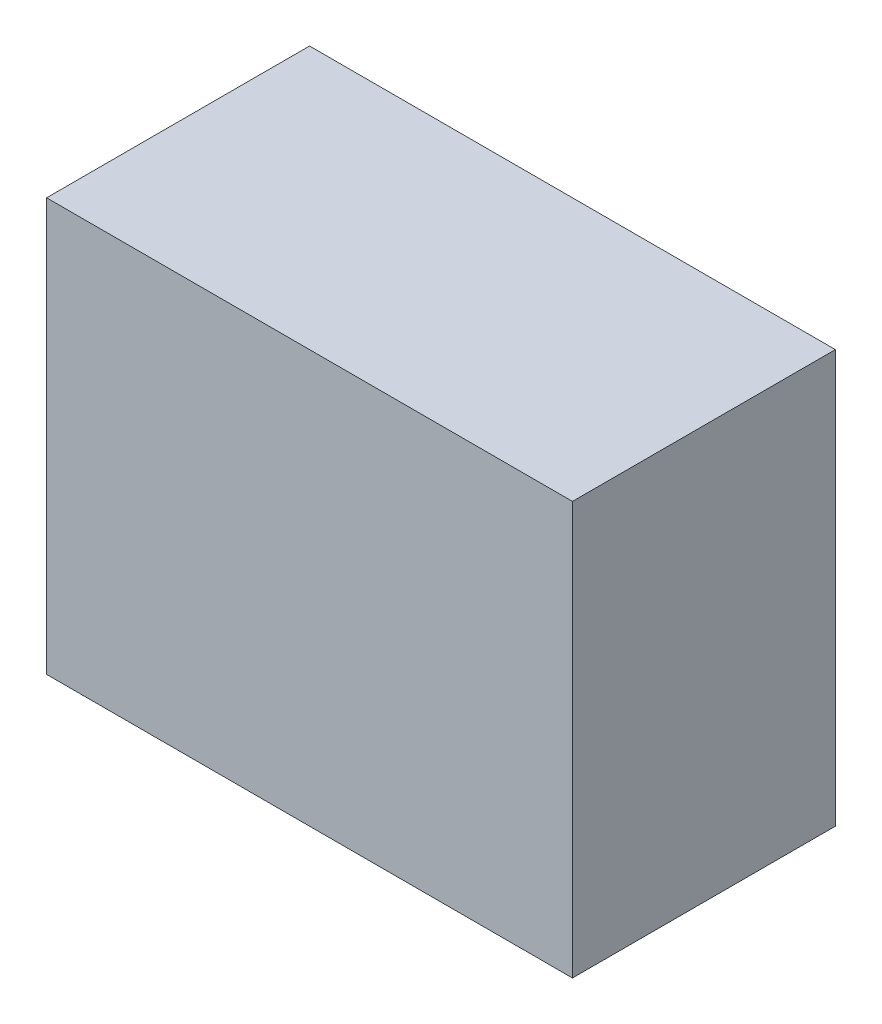
SolidWorks part; units mm, degrees
ref_plane "Front Plane" through (0, 0, 0) normal (0, 0, 1) x (1, 0, 0)
ref_plane "Top Plane" through (0, 0, 0) normal (0, 1, 0) x (1, 0, 0)
ref_plane "Right Plane" through (0, 0, 0) normal (1, 0, 0) x (0, 0, -1)
sketch "Sketch1" plane through (0, 0, 0) normal (0, 1, 0) x (1, 0, 0)
  line L1 (-25.4, 12.7) -> (25.4, 12.7)
  line L2 (-25.4, 12.7) -> (-25.4, -12.7)
  line L3 (-25.4, -12.7) -> (25.4, -12.7)
  line L4 (25.4, 12.7) -> (25.4, -12.7)
  line L5 (-25.4, 12.7) -> (25.4, -12.7) construction
  line L6 (-25.4, -12.7) -> (25.4, 12.7) construction
  point P0 (0, 0)
  dimension "D1" = 50.8
  dimension "D2" = 25.4
extrude "Boss-Extrude1" add sketch "Sketch1" along normal up to surface (39.875 mm away)
